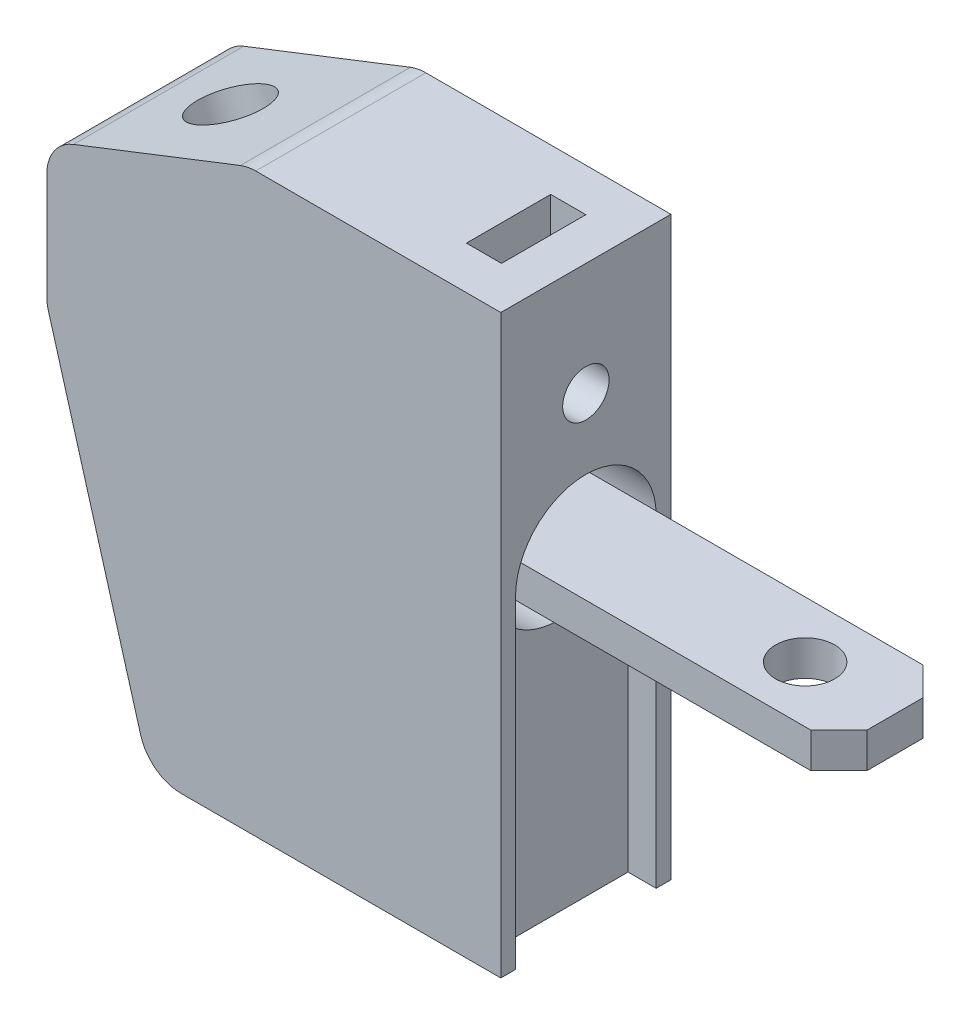
SolidWorks part; units mm, degrees
ref_plane "Спереди" through (0, 0, 0) normal (0, 0, 1) x (1, 0, 0)
ref_plane "Сверху" through (0, 0, 0) normal (0, 1, 0) x (1, 0, 0)
ref_plane "Справа" through (0, 0, 0) normal (1, 0, 0) x (0, 0, -1)
sketch "Эскиз1" plane through (0, 0, 0) normal (0, 0, 1) x (1, 0, 0)
  line L0 (0, 37.9243) -> (0, -33.4875) construction
  line L1 (0, -23) -> (0, 18)
  line L2 (0, 0) -> (19.5678, 0) construction
  line L3 (0, 18) -> (-18, 18)
  line L4 (-18, 18) -> (-32.3, 12.4139)
  line L5 (-32.3, 12.4139) -> (-32.3, 2.4139)
  line L6 (-32.3, 2.4139) -> (-25, -23)
  line L7 (-25, -23) -> (0, -23)
  dimension "D1" = 18
  dimension "D2" = 23
  dimension "D3" = 32.3
  dimension "D4" = 10
  dimension "D5" = 25
  dimension "D6" = 18
extrude "Вытянуть1" add sketch "Эскиз1" along normal blind 12.1
sketch "Эскиз2" plane through (0, 18, 0) normal (0, 1, 0) x (1, 0, 0)
  line L0 (-20.9812, -6.05) -> (0.6825, -6.05) construction
  line L1 (0, 0) -> (-18, 0) construction
  line L2 (0, -12.1) -> (-18, -12.1) construction
  line L3 (0, -12.1) -> (0, 0) construction
  line L4 (-5.5, -9.05) -> (-3, -9.05)
  line L5 (-5.5, -9.05) -> (-5.5, -3.05)
  line L6 (-5.5, -3.05) -> (-3, -3.05)
  line L7 (-3, -9.05) -> (-3, -3.05)
  dimension "D1" = 2.5
  dimension "D2" = 6
  dimension "D3" = 3
extrude "Вырез-Вытянуть1" cut sketch "Эскиз2" against normal blind 5
sketch "Эскиз3" plane through (-8.4836, 21.7174, 0) normal (-0.3639, 0.9315, 0) x (0.9315, 0.3639, 0)
  line L0 (-28.1333, -6.05) -> (-7.9391, -6.05) construction
  line L1 (-17.8928, 3.7533) -> (-17.8928, -14.4108) construction
  line L2 (-25.569, -12.1) -> (-25.569, 0) construction
  line L3 (-10.2167, -12.1) -> (-10.2167, 0) construction
  line L4 (-10.2167, 0) -> (-25.569, 0) construction
  line L5 (-10.2167, -12.1) -> (-25.569, -12.1) construction
  circle A0 centre (-18.0362, -6.05) radius 2.5
  dimension "D1" = 5
extrude "Вырез-Вытянуть2" cut sketch "Эскиз3" against normal blind 4
sketch "Эскиз4" plane through (-7.0282, 17.9916, 0) normal (-0.3639, 0.9315, 0) x (0.9315, 0.3639, 0)
  line L0 (-22.116, -10.1299) -> (-13.931, -1.9449) construction
  line L1 (-10.2167, 0) -> (-25.569, 0) construction
  line L2 (-20.0931, -7.4709) -> (-16.6153, -3.993)
  line L3 (-19.457, -8.107) -> (-15.9792, -4.6291)
  arc A0 (-20.0931, -7.4709) -> (-19.457, -8.107) centre (-18.0362, -6.05) ccw
  circle A1 centre (-18.0362, -6.05) radius 2.5
  arc A2 (-15.9792, -4.6291) -> (-16.6153, -3.993) centre (-18.0362, -6.05) ccw
  dimension "D2" = 45
  dimension "D1" = 0
extrude "Вырез-Вытянуть3" cut sketch "Эскиз4" against normal blind 3
sketch "Эскиз5" plane through (-29.1976, -8.3868, 0) normal (-0.9611, -0.2761, 0) x (0, 0, 1)
  line L0 (6.05, 15.9752) -> (6.05, -23.2217) construction
  line L1 (-7.2383, -1.9833) -> (21.3427, -1.9833) construction
  line L2 (12.1, 11.2375) -> (0, 11.2375) construction
  line L3 (12.1, -15.2041) -> (0, -15.2041) construction
  line L4 (0, 11.2375) -> (0, -15.2041) construction
  line L5 (12.1, 11.2375) -> (12.1, -15.2041) construction
  line L7 (3.05, -7.9833) -> (9.05, -7.9833)
  line L8 (3.05, -7.9833) -> (3.05, 4.0167)
  line L9 (3.05, 4.0167) -> (9.05, 4.0167)
  line L10 (9.05, -7.9833) -> (9.05, 4.0167)
  dimension "D1" = 6
  dimension "D2" = 12
extrude "Вырез-Вытянуть4" cut sketch "Эскиз5" against normal blind 5
fillet "Скругление1" radius 3 4 edges at (-25, -23, 6.05) (-32.3, 2.4139, 6.05) (-32.3, 12.4139, 6.05) (-18, 18, 6.05)
sketch "Эскиз6" plane through (0, 0, 0) normal (1, 0, 0) x (0, 0, -1)
  line L0 (-6.05, 21.5289) -> (-6.05, -25.6471) construction
  line L1 (-17.7023, 0) -> (7.5548, 0) construction
  line L2 (-12.1, -23) -> (-12.1, 18) construction
  line L3 (0, -23) -> (0, 18) construction
  circle A0 centre (-6.05, 0) radius 5
  circle A1 centre (-6.05, 10) radius 1.65
  dimension "D1" = 10
  dimension "D2" = 3.3
  dimension "D3" = 10
extrude "Вырез-Вытянуть5" cut sketch "Эскиз6" against normal blind 5
sketch "Эскиз7" plane through (-5, 0, 0) normal (1, 0, 0) x (0, 0, -1)
  line L0 (-6.05, 10) -> (-6.05, -26.5919) construction
  line L1 (-17.2614, 0) -> (4.5945, 0) construction
  line L2 (-12.1, -23) -> (-12.1, 18) construction
  line L3 (0, -23) -> (0, 18) construction
  line L5 (-10.05, -1.25) -> (-2.05, -1.25)
  line L6 (-10.05, -1.25) -> (-10.05, 1.25)
  line L7 (-10.05, 1.25) -> (-2.05, 1.25)
  line L8 (-2.05, -1.25) -> (-2.05, 1.25)
  dimension "D1" = 8
  dimension "D2" = 2.5
extrude "Вытянуть2" add sketch "Эскиз7" along normal blind 27
sketch "Эскиз8" plane through (0, 1.25, 0) normal (0, 1, 0) x (1, 0, 0)
  line L0 (2.5398, -6.05) -> (26.2788, -6.05) construction
  line L1 (22, -2.05) -> (-5, -2.05) construction
  line L2 (22, -10.05) -> (-5, -10.05) construction
  line L3 (0, -12.1) -> (0, 0) construction
  circle A0 centre (15.6, -6.05) radius 2.1
  dimension "D1" = 4.2
  dimension "D2" = 15.6
extrude "Вырез-Вытянуть6" cut sketch "Эскиз8" against normal blind 30
chamfer "Фаска1" distance 2 angle 45 2 edges at (22, 0, 10.05) (22, 0, 2.05)
sketch "Эскиз9" plane through (0, 0, 0) normal (1, 0, 0) x (0, 0, -1)
  line L0 (-12.1, -23) -> (0, -23) construction
  line L1 (-11.05, -23) -> (-1.05, -23)
  line L2 (-1.05, 0) -> (-1.05, -23)
  line L3 (-11.05, 0) -> (-11.05, -23)
  circle A0 centre (-6.05, 0) radius 5 construction
  arc A1 (-11.05, 0) -> (-1.05, 0) centre (-6.05, 0) ccw
extrude "Вырез-Вытянуть7" cut sketch "Эскиз9" against normal blind 2
